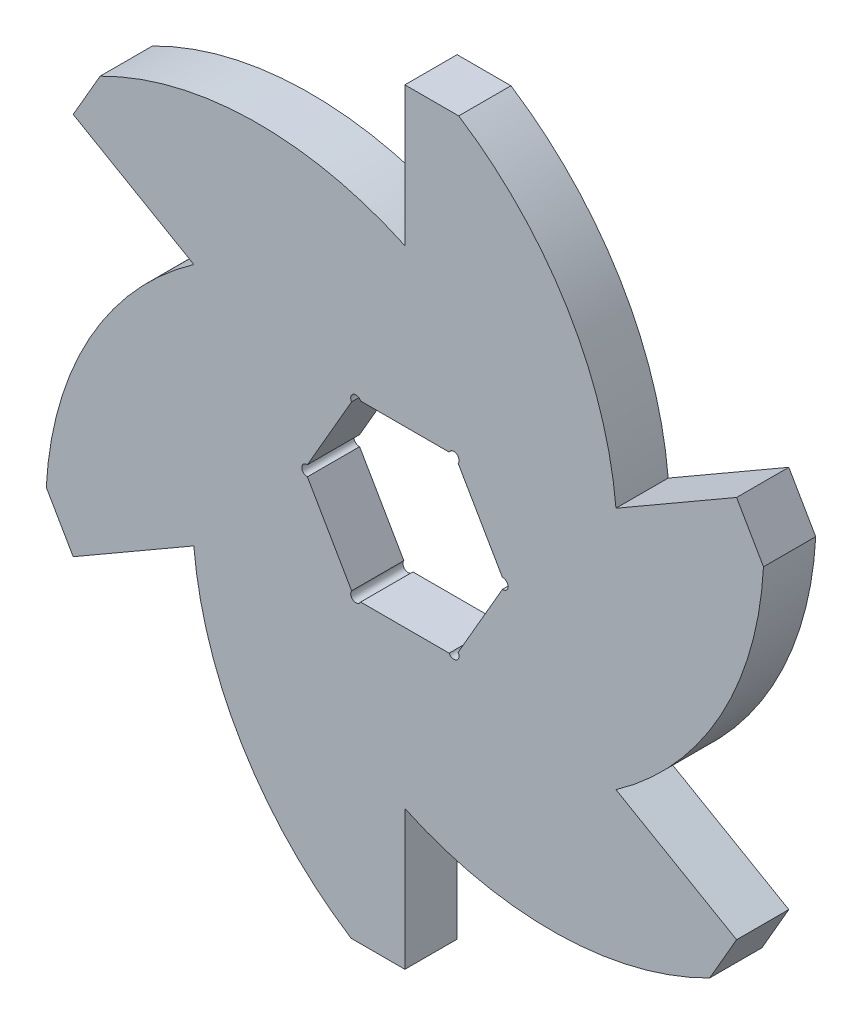
SolidWorks part; units mm, degrees
ref_plane "Front Plane" through (0, 0, 0) normal (0, 0, 1) x (1, 0, 0)
ref_plane "Top Plane" through (0, 0, 0) normal (0, 1, 0) x (1, 0, 0)
ref_plane "Right Plane" through (0, 0, 0) normal (1, 0, 0) x (0, 0, -1)
sketch "Sketch1" plane through (0, 0, 0) normal (0, 0, 1) x (1, 0, 0)
  line L0 (0, 0) -> (0, 146.8351) construction
  line L1 (-28.004, -1.4957) -> (-15.2973, -23.5043)
  line L2 (-12.7067, -25) -> (12.7067, -25)
  line L3 (15.2973, -23.5043) -> (28.004, -1.4957)
  line L4 (28.004, 1.4957) -> (15.2973, 23.5043)
  line L5 (12.7067, 25) -> (-12.7067, 25)
  line L6 (-15.2973, 23.5043) -> (-28.004, 1.4957)
  line L7 (0, 0) -> (21.4991, 152.9744) construction
  line L8 (0, 0) -> (127.1629, 73.4176) construction
  line L9 (0, 0) -> (143.2293, 57.8684) construction
  line L10 (0, 0) -> (127.1629, -73.4176) construction
  line L11 (0, 0) -> (121.7301, -95.106) construction
  line L12 (0, 0) -> (0, -146.8351) construction
  line L13 (0, 0) -> (-21.4991, -152.9744) construction
  line L14 (0, 0) -> (-127.1629, -73.4176) construction
  line L15 (0, 0) -> (-143.2293, -57.8684) construction
  line L16 (0, 0) -> (-127.1629, 73.4176) construction
  line L17 (0, 0) -> (-121.7301, 95.106) construction
  line L18 (0, 70) -> (0, 110)
  line L19 (0, 110) -> (15.4595, 110)
  line L20 (60.6218, 35) -> (95.2628, 55)
  line L21 (95.2628, 55) -> (102.9925, 41.6117)
  line L22 (60.6218, -35) -> (95.2628, -55)
  line L23 (95.2628, -55) -> (87.533, -68.3883)
  line L24 (0, -70) -> (0, -110)
  line L25 (0, -110) -> (-15.4595, -110)
  line L26 (-60.6218, -35) -> (-95.2628, -55)
  line L27 (-95.2628, -55) -> (-102.9925, -41.6117)
  line L28 (-60.6218, 35) -> (-95.2628, 55)
  line L29 (-95.2628, 55) -> (-87.533, 68.3883)
  circle A0 centre (0, 0) radius 25 construction
  arc A1 (-28.004, 1.4957) -> (-28.004, -1.4957) centre (-28.1175, 0) ccw
  arc A2 (-12.7067, 25) -> (-15.2973, 23.5043) centre (-14.0588, 24.3505) ccw
  arc A3 (15.2973, 23.5043) -> (12.7067, 25) centre (14.0588, 24.3505) ccw
  arc A4 (28.004, -1.4957) -> (28.004, 1.4957) centre (28.1175, 0) ccw
  arc A5 (12.7067, -25) -> (15.2973, -23.5043) centre (14.0588, -24.3505) ccw
  arc A6 (-15.2973, -23.5043) -> (-12.7067, -25) centre (-14.0588, -24.3505) ccw
  circle A7 centre (0, 0) radius 70 construction
  arc A8 (15.4595, 110) -> (60.6218, 35) centre (-38.9831, 26.1191) cw
  arc A9 (102.9925, 41.6117) -> (60.6218, -35) centre (3.1283, 46.8199) cw
  arc A10 (87.533, -68.3883) -> (0, -70) centre (42.1113, 20.7008) cw
  arc A11 (-15.4595, -110) -> (-60.6218, -35) centre (38.9831, -26.1191) cw
  arc A12 (-102.9925, -41.6117) -> (-60.6218, 35) centre (-3.1283, -46.8199) cw
  arc A13 (-87.533, 68.3883) -> (0, 70) centre (-42.1113, -20.7008) cw
  point P24 (0, 0)
  point P38 (0, 0)
  point P68 (0, 0)
  dimension "D1" = 50
  dimension "D3" = 3
  dimension "D2" = 140
  dimension "D8" = 100
  dimension "D5" = 8
  dimension "D7" = 40
  dimension "D4" = 6
  dimension "D6" = 6
  dimension "D9" = 6
extrude "Boss-Extrude1" add sketch "Sketch1" along normal blind 15
